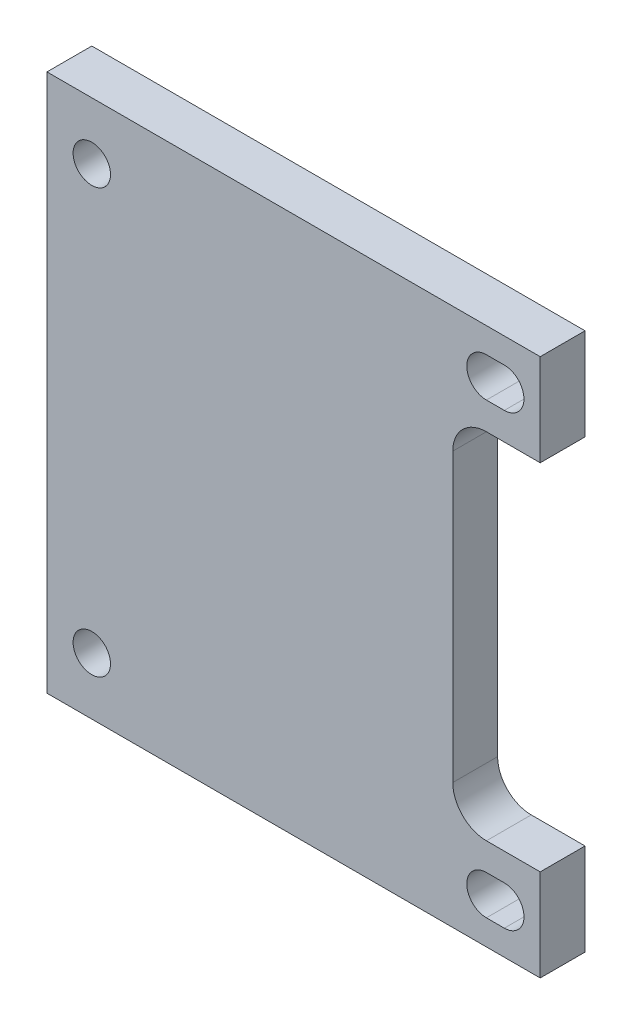
SolidWorks part; units mm, degrees
ref_plane "Front Plane" through (0, 0, 0) normal (0, 0, 1) x (1, 0, 0)
ref_plane "Top Plane" through (0, 0, 0) normal (0, 1, 0) x (1, 0, 0)
ref_plane "Right Plane" through (0, 0, 0) normal (1, 0, 0) x (0, 0, -1)
sketch "Sketch1" plane through (0, 0, 0) normal (0, 0, 1) x (1, 0, 0)
  line L1 (0, 0) -> (69.85, 0)
  line L2 (0, 0) -> (0, 76.2)
  line L3 (0, 76.2) -> (69.85, 76.2)
  line L4 (69.85, 0) -> (69.85, 76.2)
  dimension "D1" = 69.85
  dimension "D2" = 76.2
extrude "Boss-Extrude1" add sketch "Sketch1" along normal blind 6.35
sketch "Sketch2" plane through (0, 0, 6.35) normal (0, 0, 1) x (1, 0, 0)
  line L0 (6.35, 76.2) -> (6.35, 0) construction
  line L1 (69.85, 76.2) -> (0, 76.2) construction
  line L2 (0, 0) -> (69.85, 0) construction
  line L3 (0, 38.1) -> (69.85, 38.1) construction
  line L4 (0, 76.2) -> (0, 0) construction
  line L5 (69.85, 0) -> (69.85, 76.2) construction
  point P6 (6.35, 68.1)
  point P7 (6.35, 8.1)
  dimension "D1" = 60
  dimension "D2" = 6.35
hole_wizard "M5 Clearance Hole1" positions "3DSketch1" profile "Sketch3" hole size "M5" standard "ANSI Metric"
sketch3d "3DSketch1"
  point P0 (6.35, 68.1, 6.35)
  point P3 (6.35, 8.1, 6.35)
sketch "Sketch3" plane through (6.35, 68.1, 6.35) normal (1, 0, 0) x (0, -1, 0)
  line L0 (0, 0) -> (0, 7.9423)
  line L1 (0, 7.9423) -> (2.65, 6.35)
  line L2 (2.65, 6.35) -> (2.65, 0)
  line L5 (2.65, 0) -> (0, 0)
  line L10 (0, 7.9423) -> (-2.65, 6.35) construction
  line L11 (0, -6.35) -> (0, 107.95) construction
  dimension "Hole Dia." = 5.3
  dimension "Hole Depth" = 6.35
  dimension "Drill Angle" = 118
sketch "Sketch4" plane through (0, 0, 6.35) normal (0, 0, 1) x (1, 0, 0)
  line L0 (64.77, 76.2) -> (64.77, 0) construction
  line L1 (69.85, 76.2) -> (0, 76.2) construction
  line L2 (0, 0) -> (69.85, 0) construction
  line L3 (69.85, 38.1) -> (0, 38.1) construction
  line L4 (69.85, 0) -> (69.85, 76.2) construction
  line L5 (0, 76.2) -> (0, 0) construction
  line L6 (64.77, 69.85) -> (62.23, 69.85) construction
  line L7 (64.77, 67.0719) -> (62.23, 67.0719)
  line L8 (64.77, 72.6281) -> (62.23, 72.6281)
  line L9 (64.77, 6.35) -> (62.23, 6.35) construction
  line L10 (64.77, 9.1281) -> (62.23, 9.1281)
  line L11 (64.77, 3.5719) -> (62.23, 3.5719)
  arc A0 (64.77, 67.0719) -> (64.77, 72.6281) centre (64.77, 69.85) ccw
  arc A1 (62.23, 72.6281) -> (62.23, 67.0719) centre (62.23, 69.85) ccw
  arc A2 (64.77, 9.1281) -> (64.77, 3.5719) centre (64.77, 6.35) cw
  arc A3 (62.23, 3.5719) -> (62.23, 9.1281) centre (62.23, 6.35) cw
  point P12 (64.77, 69.85)
  point P13 (64.77, 6.35)
  point P16 (63.5, 69.85)
  point P23 (63.5, 6.35)
  dimension "D3" = 2.54
  dimension "D1" = 5.08
  dimension "D2" = 63.5
  dimension "D4" = 5.5562
extrude "Cut-Extrude1" cut sketch "Sketch4" against normal through all
sketch "Sketch5" plane through (0, 0, 6.35) normal (0, 0, 1) x (1, 0, 0)
  line L0 (69.85, 38.1) -> (0, 38.1) construction
  line L1 (69.85, 0) -> (69.85, 76.2) construction
  line L2 (0, 76.2) -> (0, 0) construction
  line L3 (62.23, 17.78) -> (62.23, 58.42) construction
  line L4 (57.4675, 17.78) -> (57.4675, 58.42)
  line L5 (66.9925, 17.78) -> (66.9925, 58.42)
  line L6 (62.23, 63.1825) -> (69.85, 63.1825)
  line L7 (62.23, 13.0175) -> (69.85, 13.0175)
  line L8 (69.85, 13.0175) -> (69.85, 63.1825)
  arc A0 (57.4675, 17.78) -> (66.9925, 17.78) centre (62.23, 17.78) ccw
  arc A1 (66.9925, 58.42) -> (57.4675, 58.42) centre (62.23, 58.42) ccw
  point P8 (62.23, 38.1)
  line M13 (69.85, 0) -> (69.85, 76.2)
  dimension "D1" = 9.525
  dimension "D2" = 40.64
  dimension "D3" = 7.62
extrude "Cut-Extrude2" cut sketch "Sketch5" against normal through all contours L5 A1 L4 A0 | A1 L5 A0 L7 L6 M13
